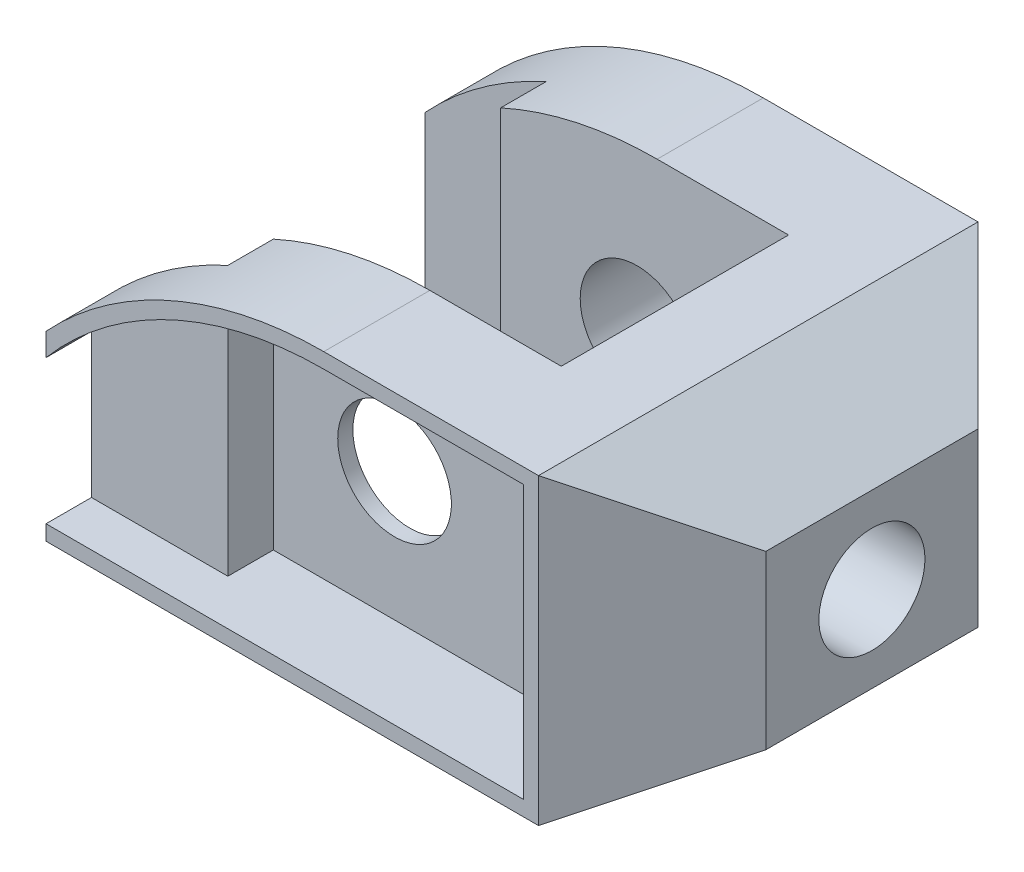
SolidWorks part; units mm, degrees
material "Alliage 1060"
ref_plane "Plan de face" through (0, 0, 0) normal (0, 0, 1) x (1, 0, 0)
ref_plane "Plan de dessus" through (0, 0, 0) normal (0, 1, 0) x (1, 0, 0)
ref_plane "Plan de droite" through (0, 0, 0) normal (1, 0, 0) x (0, 0, -1)
sketch "Esquisse1" plane through (0, 0, 0) normal (0, 0, 1) x (1, 0, 0)
  line L7 (0, 0) -> (0, 24)
  line L8 (36.6606, 40) -> (65, 40)
  line L9 (65, 40) -> (80, 31.3397)
  line L10 (80, 31.3397) -> (80, 8.6603)
  line L11 (80, 8.6603) -> (65, 0)
  line L12 (65, 0) -> (0, 0)
  arc A1 (0, 24) -> (36.6606, 40) centre (36.6606, -10) cw
  circle A2 centre (34, 19) radius 7.5
  dimension "D10" = 15
  dimension "D11" = 50
  dimension "D1" = 40
  dimension "D2" = 65
  dimension "D3" = 15
  dimension "D4" = 15
  dimension "D5" = 30
  dimension "D6" = 30
  dimension "D7" = 31
  dimension "D8" = 19
  dimension "D9" = 24
extrude "Boss.-Extru.1" add sketch "Esquisse1" along normal blind 58
sketch "Esquisse3" plane through (0, 0, 0) normal (0, -1, 0) x (1, 0, 0)
  line L0 (0, 50) -> (16, 50)
  line L1 (0, 58) -> (0, 0) construction
  line L2 (16, 50) -> (16, 44)
  line L3 (16, 44) -> (54, 44)
  line L4 (54, 44) -> (54, 14)
  line L5 (54, 14) -> (16, 14)
  line L6 (16, 14) -> (16, 8)
  line L7 (16, 8) -> (0, 8)
  line L8 (65, 58) -> (65, 0) construction
  line L9 (0, 8) -> (0, 50)
  dimension "D1" = 8
  dimension "D2" = 6
  dimension "D3" = 16
  dimension "D4" = 11
  dimension "D5" = 16
  dimension "D6" = 6
  dimension "D7" = 8
extrude "Enlèv. mat.-Extru.1" cut sketch "Esquisse3" against normal through all contours L9 L0 L2 L3 L4 L5 L6 L7
sketch "Esquisse5" plane through (0, 40, 0) normal (0, 1, 0) x (1, 0, 0)
  line L0 (65, 0) -> (80, 0)
  line L1 (80, 0) -> (80, -15)
  line L2 (80, -58) -> (80, 0) construction
  line L3 (80, -15) -> (65, 0)
  line L4 (65, -58) -> (80, -58)
  line L5 (80, -58) -> (65, -58) construction
  line L6 (65, -58) -> (65, 0) construction
  line L7 (80, -58) -> (80, -43)
  line L8 (80, -43) -> (65, -58)
  dimension "D1" = 45
  dimension "D2" = 45
extrude "Enlèv. mat.-Extru.2" cut sketch "Esquisse5" against normal through all
sketch "Esquisse6" plane through (80, 0, 0) normal (1, 0, 0) x (0, 0, -1)
  line L0 (-58, 0) -> (-58, 40) construction
  line L1 (-58, 0) -> (0, 0) construction
  circle A0 centre (-29, 20) radius 7
  dimension "D1" = 14
  dimension "D2" = 29
  dimension "D3" = 20
extrude "Enlèv. mat.-Extru.3" cut sketch "Esquisse6" against normal through all
sketch "Esquisse7" plane through (0, 0, 58) normal (0, 0, 1) x (1, 0, 0)
  line L8 (18, 34.2242) -> (18, 2)
  line L11 (0, 2) -> (63, 2)
  line L12 (63, 2) -> (63, 38)
  line L13 (63, 38) -> (36.6606, 38)
  line L14 (18, 2) -> (63, 2)
  line L15 (63, 2) -> (63, 38)
  line L16 (63, 38) -> (36.6606, 38)
  arc A3 (36.6606, 38) -> (1.4664, 22.64) centre (36.6606, -10) ccw
  arc A4 (36.6606, 38) -> (18, 34.2242) centre (36.6606, -10) ccw
  dimension "D1" = 2
extrude "Enlèv. mat.-Extru.4" cut sketch "Esquisse7" against normal offset from surface (12 mm away) 2 contours L14 L15 L16 A4 L8 up to face at (26.5, 19, 44)
sketch "Esquisse8" plane through (0, 0, 58) normal (0, 0, 1) x (1, 0, 0)
  line L1 (-4.6647, 2) -> (-4.6647, 14.4176)
  line L2 (0, 2) -> (65, 2)
  line L3 (-4.6647, 2) -> (18, 2)
  line L4 (18, 34.2242) -> (18, 2)
  line L5 (18, 34.2242) -> (18, 2) construction
  arc A2 (36.6606, 38) -> (1.4664, 22.64) centre (36.6606, -10) ccw
  arc A3 (18, 34.2242) -> (-4.6647, 14.4176) centre (36.6606, -10) ccw
  dimension "D1" = 2
  dimension "D2" = 2
extrude "Enlèv. mat.-Extru.5" cut sketch "Esquisse8" against normal offset from surface (6 mm away) 2 up to face at (7.8564, 15.0821, 50)
equation "\"A\"= 58"
equation "\"B\"= 40"
equation "\"C\"= 65"
equation "\"D1@Esquisse1\"=\"B\""
equation "\"D2@Esquisse1\"=\"C\""
equation "\"D1@Boss.-Extru.1\"=\"A\""
equation "\"D2@Esquisse6\"=\"A\"/2"
equation "\"D3@Esquisse6\"=\"B\"/2"
